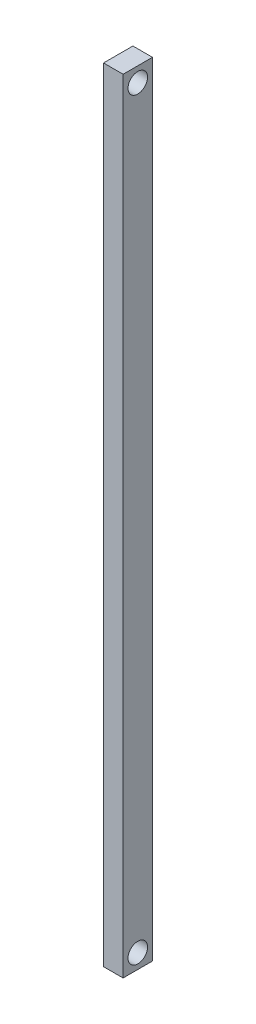
SolidWorks part; units mm, degrees
material "Plain Carbon Steel"
ref_plane "Front Plane" through (0, 0, 0) normal (1, 0, 0) x (0, 1, 0)
ref_plane "Top Plane" through (0, 0, 0) normal (0, 0, 1) x (0, 1, 0)
ref_plane "Right Plane" through (0, 0, 0) normal (0, 1, 0) x (-1, 0, 0)
sketch "Sketch1" plane through (0, 0, 0) normal (1, 0, 0) x (0, 1, 0)
  line L0 (0, 0) -> (400, 0)
  line L1 (400, 0) -> (400, 15)
  line L2 (400, 15) -> (0, 15)
  line L3 (0, 15) -> (0, 0)
  dimension "D1" = 15
  dimension "D2" = 400
extrude "Boss-Extrude1" add sketch "Sketch1" along normal blind 10
sketch "Sketch3" plane through (0, 0, 0) normal (1, 0, 0) x (0, 1, 0)
  line L0 (400, 15) -> (0, 15) construction
  line L1 (0, 15) -> (0, 0) construction
  circle A0 centre (7.5, 7.5) radius 5
  dimension "D1" = 10
  dimension "D2" = 7.5
  dimension "D3" = 7.5
extrude "Cut-Extrude1" cut sketch "Sketch3" along normal blind 10
sketch "Sketch4" plane through (10, 0, 0) normal (1, 0, 0) x (0, 1, 0)
  line L0 (400, 15) -> (0, 15) construction
  line L1 (400, 0) -> (400, 15) construction
  circle A0 centre (392.5, 7.5) radius 5
  dimension "D2" = 10
  dimension "D3" = 7.5
  dimension "D1" = 7.5
extrude "Cut-Extrude2" cut sketch "Sketch4" against normal blind 10 contours A0
